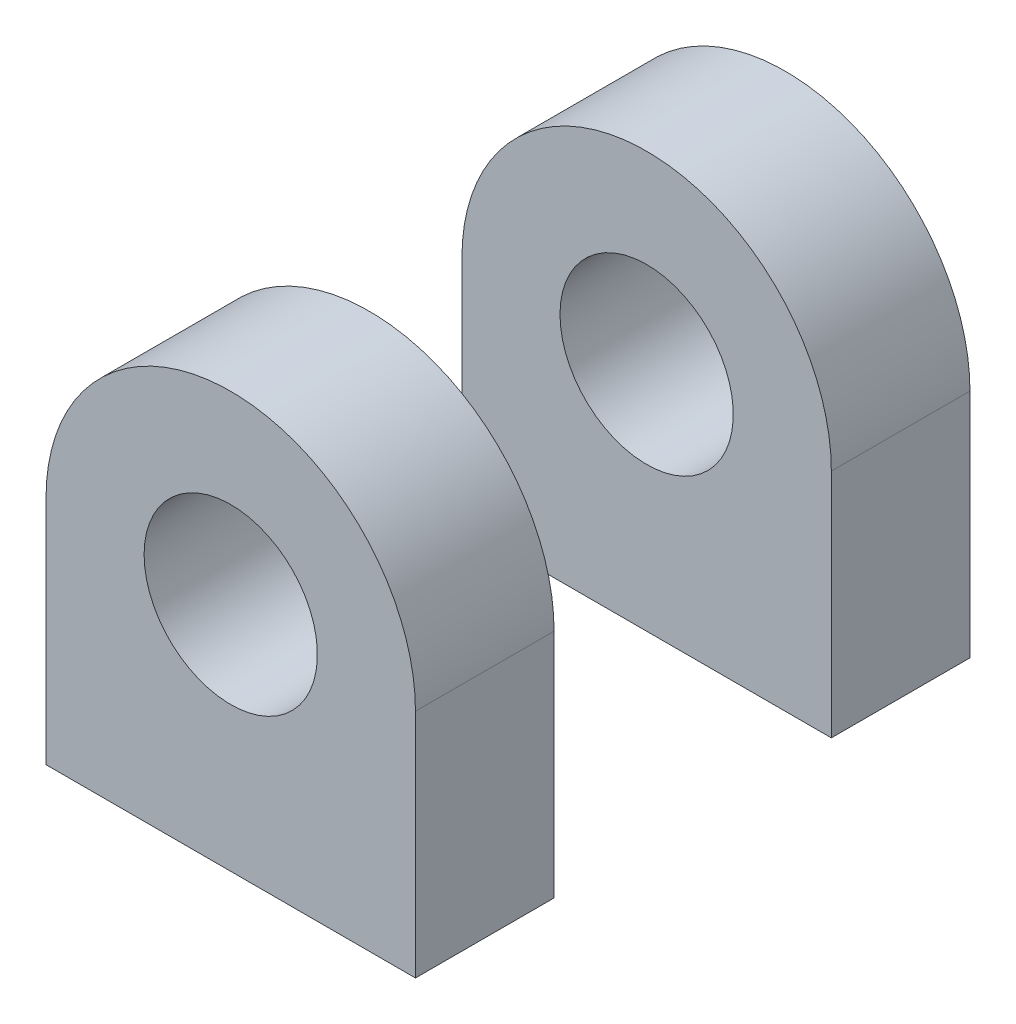
SolidWorks part; units mm, degrees
ref_plane "Front Plane" through (0, 0, 0) normal (0, 0, 1) x (1, 0, 0)
ref_plane "Top Plane" through (0, 0, 0) normal (0, 1, 0) x (1, 0, 0)
ref_plane "Right Plane" through (0, 0, 0) normal (1, 0, 0) x (0, 0, -1)
sketch "Sketch1" plane through (0, 0, 0) normal (0, 0, 1) x (1, 0, 0)
  line L1 (0, 0) -> (10.1533, 0)
  line L2 (0, 0) -> (0, 6.35)
  line L4 (10.1533, 0) -> (10.1533, 6.35)
  arc A0 (0, 6.35) -> (10.1533, 6.35) centre (5.0767, 6.35) cw
  circle A1 centre (5.0767, 6.35) radius 2.3813
  dimension "D1" = 4.7625
  dimension "D3" = 5.0767
  dimension "D2" = 6.35
extrude "Boss-Extrude1" add sketch "Sketch1" along normal mid plane 15.24 contours A0 L2 L1 L4 A1
sketch "Sketch2" plane through (0, 0, 0) normal (-1, 0, 0) x (0, 0, 1)
  line L0 (-7.62, 0) -> (-7.62, 6.35) construction
  line L1 (-3.81, 0) -> (3.81, 0)
  line L2 (-3.81, 0) -> (-3.81, 24.1712)
  line L3 (-3.81, 24.1712) -> (3.81, 24.1712)
  line L4 (3.81, 0) -> (3.81, 24.1712)
  line L5 (7.62, 0) -> (7.62, 6.35) construction
  line L6 (7.62, 0) -> (-7.62, 0) construction
  dimension "D1" = 3.81
  dimension "D2" = 3.81
  dimension "D3" = 0
  dimension "D4" = 24.1712
extrude "Cut-Extrude1" cut sketch "Sketch2" against normal blind 25.4 contours L2 L1 L4 L3
